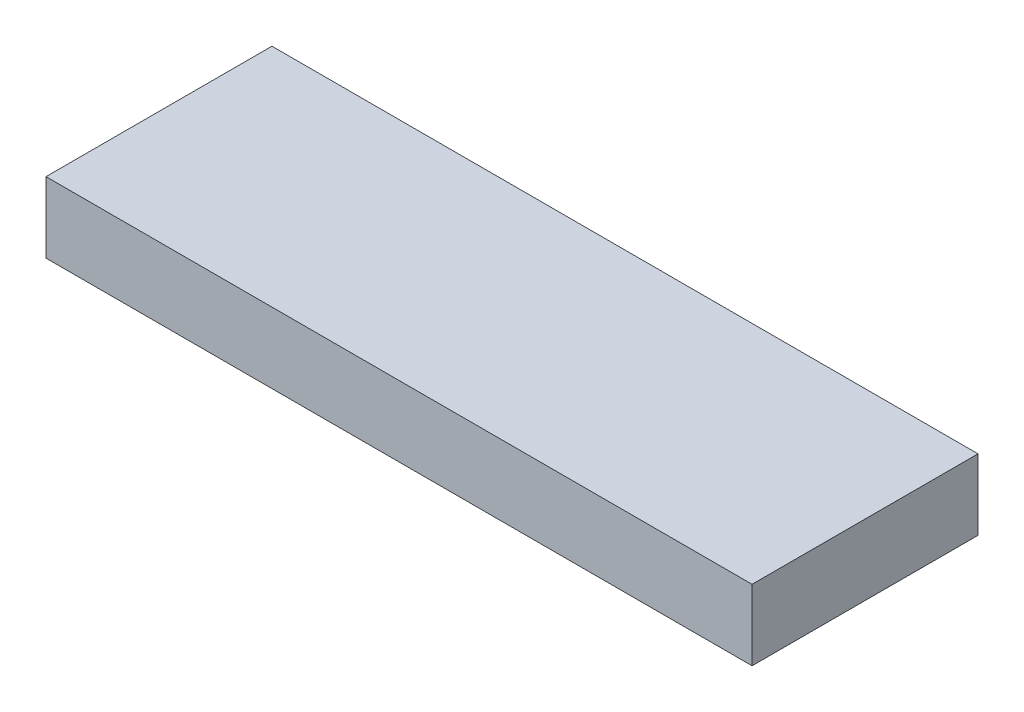
SolidWorks part; units mm, degrees
ref_plane "前视基准面" through (0, 0, 0) normal (0, 0, 1) x (1, 0, 0)
ref_plane "上视基准面" through (0, 0, 0) normal (0, 1, 0) x (1, 0, 0)
ref_plane "右视基准面" through (0, 0, 0) normal (1, 0, 0) x (0, 0, -1)
other "Configuration Table"
sketch "草图1" plane through (0, 0, 0) normal (1, 0, 0) x (0, 0, -1)
  line L1 (-8, 2.5) -> (8, 2.5)
  line L2 (-8, 2.5) -> (-8, -2.5)
  line L3 (-8, -2.5) -> (8, -2.5)
  line L4 (8, 2.5) -> (8, -2.5)
  line L5 (-8, 2.5) -> (8, -2.5) construction
  line L6 (-8, -2.5) -> (8, 2.5) construction
  point P0 (0, 0)
  dimension "D1" = 16
  dimension "D2" = 5
extrude "凸台-拉伸1" add sketch "草图1" along normal blind 50 contours L1 L4 L3 L2
